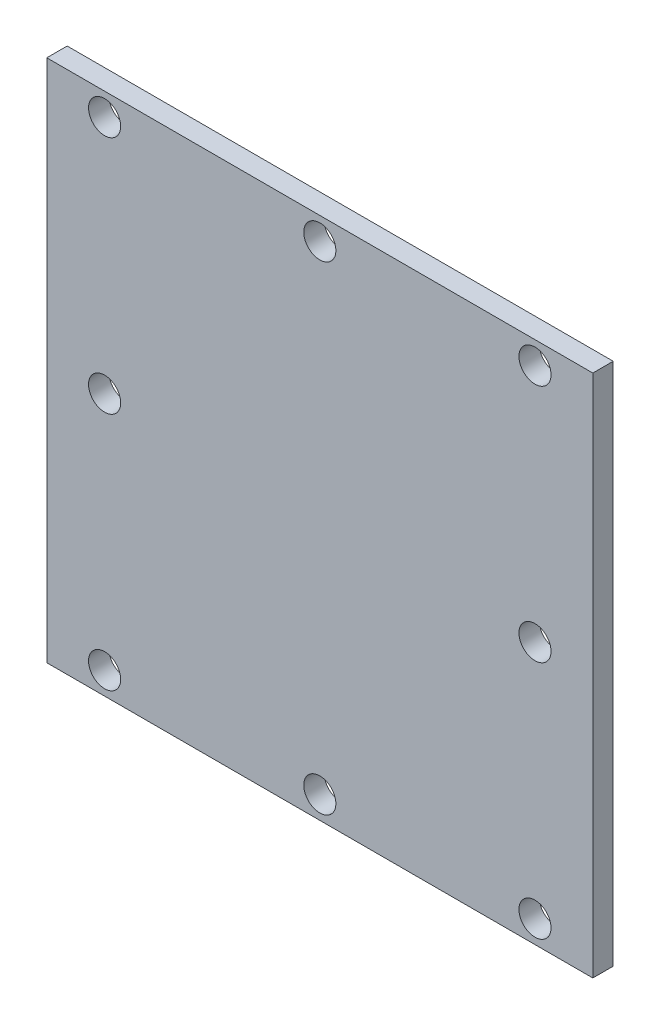
SolidWorks part; units mm, degrees
material "AISI 1020 Steel, Cold Rolled"
ref_plane "Front Plane" through (0, 0, 0) normal (0, 0, 1) x (1, 0, 0)
ref_plane "Top Plane" through (0, 0, 0) normal (0, 1, 0) x (1, 0, 0)
ref_plane "Right Plane" through (0, 0, 0) normal (1, 0, 0) x (0, 0, -1)
sketch "Sketch1" plane through (0, 0, 0) normal (0, 0, 1) x (1, 0, 0)
  line L4 (0, 0) -> (0, 163.12)
  line L5 (0, 163.12) -> (170, 163.12)
  line L6 (170, 163.12) -> (170, 0)
  line L7 (170, 0) -> (0, 0)
  circle A0 centre (85, 7) radius 5
  circle A1 centre (152, 7) radius 5
  circle A2 centre (18, 7) radius 5
  circle A3 centre (18, 81.56) radius 5
  circle A4 centre (18, 156.12) radius 5
  circle A5 centre (152, 81.56) radius 5
  circle A6 centre (152, 156.12) radius 5
  circle A7 centre (85, 156.12) radius 5
  point P0 (0, 0)
  point P1 (85, 0)
  point P2 (170, 81.56)
  dimension "D4" = 10
  dimension "D7" = 170
  dimension "D1" = 7
  dimension "D2" = 18
  dimension "D5" = 7
  dimension "D6" = 18
  dimension "D3" = 163.12
extrude "Boss-Extrude1" add sketch "Sketch1" against normal blind 6.35
